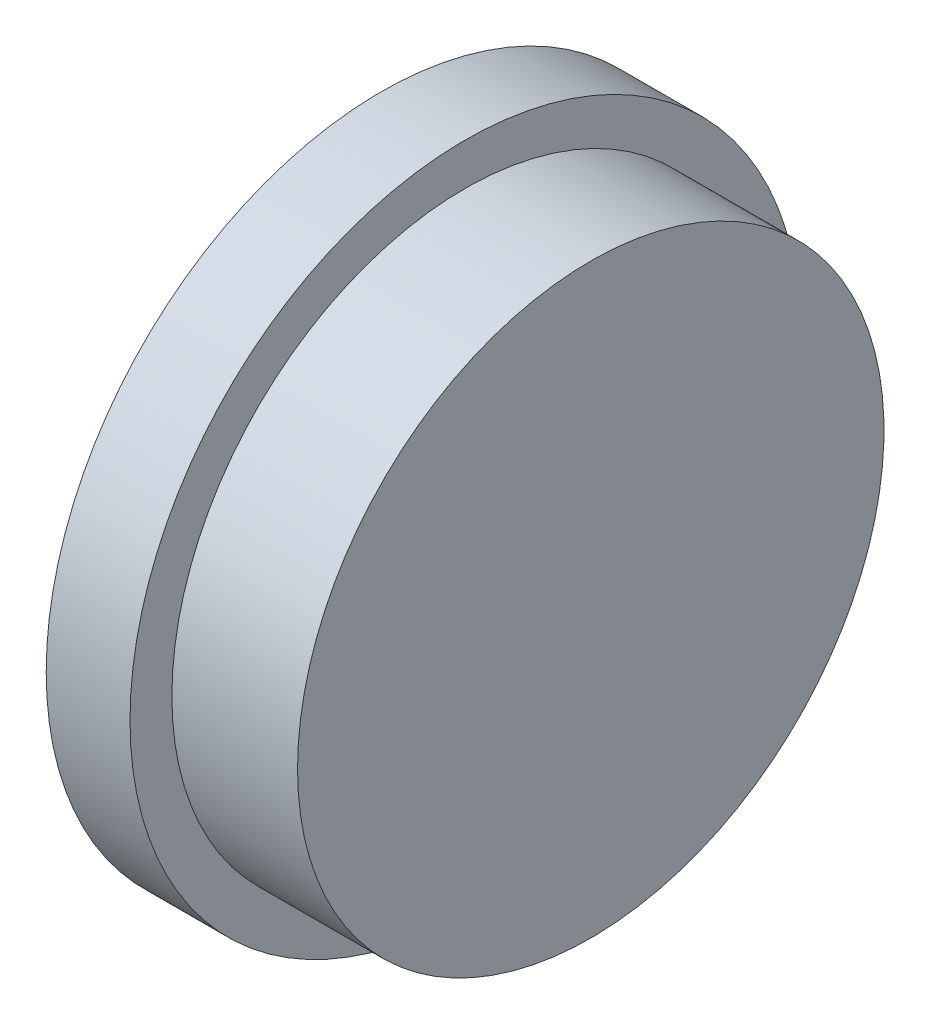
SolidWorks part; units mm, degrees
ref_plane "Plan de face" through (0, 0, 0) normal (0, 0, 1) x (1, 0, 0)
ref_plane "Plan de dessus" through (0, 0, 0) normal (0, 1, 0) x (1, 0, 0)
ref_plane "Plan de droite" through (0, 0, 0) normal (1, 0, 0) x (0, 0, -1)
sketch "Esquisse1" plane through (0, 0, 0) normal (0, 0, 1) x (1, 0, 0)
  line L0 (0, 0) -> (150, 0) construction
  line L1 (150, 0) -> (150, 210)
  line L2 (150, 210) -> (60, 210)
  line L3 (60, 210) -> (60, 240)
  line L4 (60, 240) -> (0, 240)
  line L5 (0, 240) -> (0, 160)
  line L6 (0, 160) -> (130, 160)
  line L7 (130, 160) -> (130, 0)
  line L8 (130, 0) -> (150, 0)
  dimension "D1" = 60
  dimension "D2" = 80
  dimension "D3" = 160
  dimension "D4" = 150
  dimension "D5" = 130
  dimension "D6" = 210
revolve "Révolution1" add sketch "Esquisse1" angle 360 about L0
